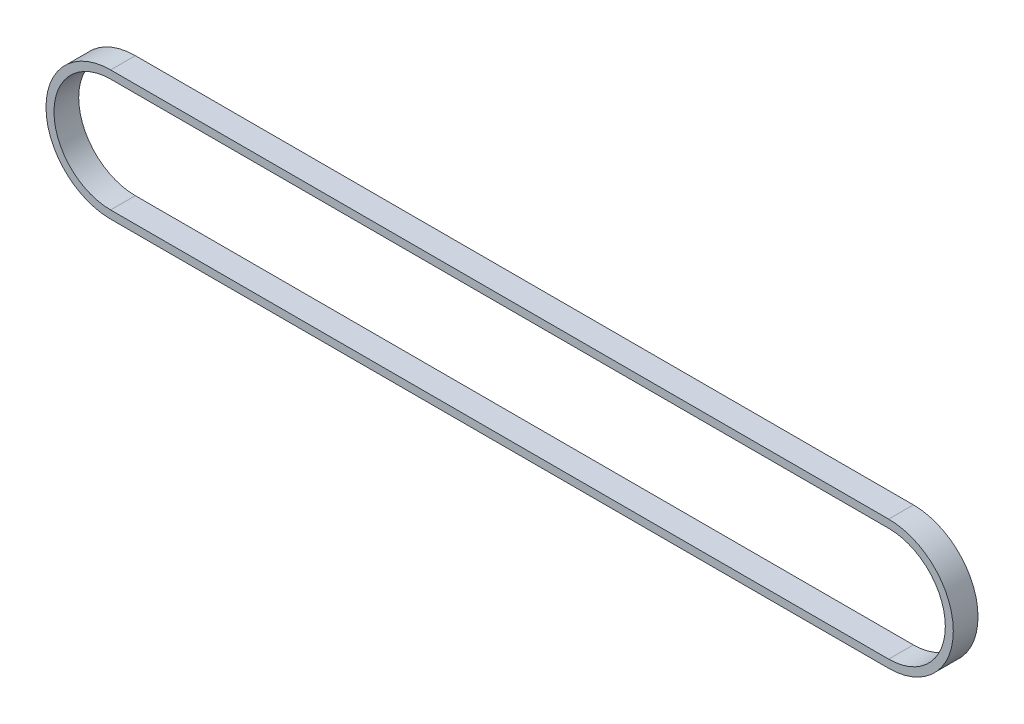
SolidWorks part; units mm, degrees
material "ﾆﾄﾘﾙｺﾞﾑ(NBR)"
ref_plane "正面" through (0, 0, 0) normal (0, 0, 1) x (1, 0, 0)
ref_plane "平面" through (0, 0, 0) normal (0, 1, 0) x (1, 0, 0)
ref_plane "右側面" through (0, 0, 0) normal (1, 0, 0) x (0, 0, -1)
sketch "ｽｹｯﾁ1" plane through (0, 0, 0) normal (0, 0, 1) x (1, 0, 0)
  line L0 (-89, 7.5) -> (100, 7.5) construction
  line L1 (-89, 22.78) -> (100, 22.78) construction
  line L2 (-89, -7.78) -> (100, -7.78) construction
  line L3 (-89, 23.199) -> (100, 23.199)
  line L4 (-89, -8.199) -> (100, -8.199)
  line L5 (-89, 21.259) -> (100, 21.259)
  line L6 (-89, -6.259) -> (100, -6.259)
  arc A0 (-89, 22.78) -> (-89, -7.78) centre (-89, 7.5) ccw construction
  arc A1 (100, -7.78) -> (100, 22.78) centre (100, 7.5) ccw construction
  arc A2 (100, -8.199) -> (100, 23.199) centre (100, 7.5) ccw
  arc A3 (-89, 23.199) -> (-89, -8.199) centre (-89, 7.5) ccw
  arc A4 (100, -6.259) -> (100, 21.259) centre (100, 7.5) ccw
  arc A5 (-89, 21.259) -> (-89, -6.259) centre (-89, 7.5) ccw
  point P4 (5.5, 7.5)
  dimension "D1" = 30.56
  dimension "D2" = 0.419
  dimension "D3" = 1.94
extrude "ﾎﾞｽ - 押し出し1" add sketch "ｽｹｯﾁ1" along normal mid plane 6
